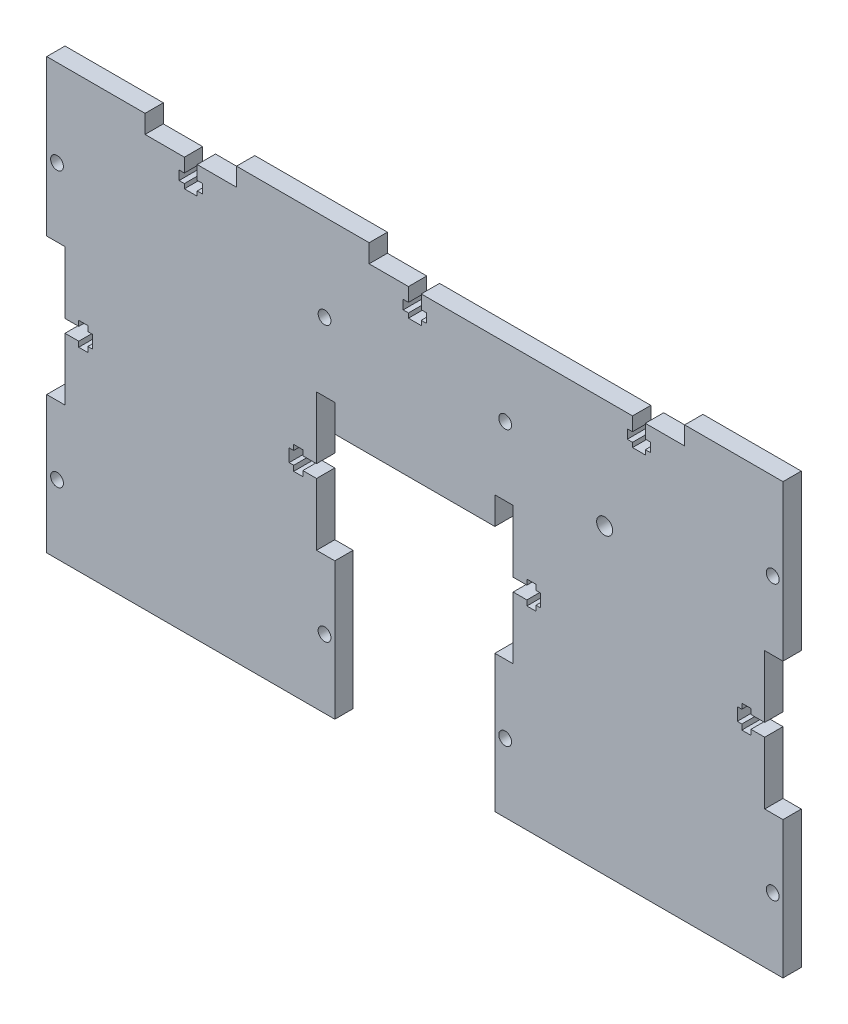
SolidWorks part; units mm, degrees
ref_plane "Спереди" through (0, 0, 0) normal (0, 0, 1) x (1, 0, 0)
ref_plane "Сверху" through (0, 0, 0) normal (0, 1, 0) x (1, 0, 0)
ref_plane "Справа" through (0, 0, 0) normal (1, 0, 0) x (0, 0, -1)
sketch "Эскиз1" plane through (0, 0, 0) normal (0, 0, 1) x (1, 0, 0)
  line L0 (-78.25, -14) -> (-78.25, 16) construction
  line L22 (78.25, -44) -> (78.25, -74) construction
  line L47 (-26.5, -26.45) -> (-24.5, -31.55) construction
  line L76 (-17.5, -20) -> (17.5, -20)
  line L93 (-17.5, -20) -> (-17.5, 20)
  line L126 (-17.5, 20) -> (17.5, 20)
  line L135 (17.5, -20) -> (17.5, 20)
  line L136 (-17.5, -20) -> (17.5, 20) construction
  line L141 (-17.5, 20) -> (17.5, -20) construction
  line L154 (-17.5, 20) -> (-80.5, 20)
  line L167 (-17.5, 20) -> (-17.5, -74)
  line L168 (-17.5, -74) -> (-80.5, -74)
  line L169 (-80.5, 20) -> (-80.5, -74)
  line L186 (-80.5, -14) -> (-76.5, -14)
  line L191 (-80.5, -14) -> (-80.5, -44)
  line L192 (-80.5, -44) -> (-76.5, -44)
  line L193 (-76.5, -14) -> (-76.5, -44)
  line L198 (-49, -74) -> (-49, 16) construction
  line L199 (-80.5, -29) -> (-17.5, -29) construction
  line L201 (-70.5, -30.4) -> (-76.5, -30.4)
  line L202 (-70.5, -30.4) -> (-70.5, -27.6)
  line L203 (-70.5, -27.6) -> (-76.5, -27.6)
  line L204 (-76.5, -30.4) -> (-76.5, -27.6)
  line L205 (-70.5, -30.4) -> (-76.5, -27.6) construction
  line L206 (-70.5, -27.6) -> (-76.5, -30.4) construction
  line L207 (-71.5, -31.55) -> (-73.5, -31.55)
  line L208 (-71.5, -31.55) -> (-71.5, -26.45)
  line L209 (-71.5, -26.45) -> (-73.5, -26.45)
  line L210 (-73.5, -31.55) -> (-73.5, -26.45)
  line L211 (-71.5, -31.55) -> (-73.5, -26.45) construction
  line L212 (-71.5, -26.45) -> (-73.5, -31.55) construction
  line L216 (-59, 16) -> (-39, 16)
  line L221 (-59, 16) -> (-59, 20)
  line L222 (-59, 20) -> (-39, 20)
  line L223 (-39, 16) -> (-39, 20)
  line L224 (-59, 16) -> (-39, 20) construction
  line L225 (-59, 20) -> (-39, 16) construction
  line L226 (-10, 16) -> (10, 16)
  line L227 (-10, 16) -> (-10, 20)
  line L228 (-10, 20) -> (10, 20)
  line L229 (10, 16) -> (10, 20)
  line L230 (-10, 16) -> (10, 20) construction
  line L231 (-10, 20) -> (10, 16) construction
  line L232 (-26.5, -31.55) -> (-24.5, -26.45) construction
  line L233 (-27.5, -27.6) -> (-21.5, -30.4) construction
  line L234 (-27.5, -30.4) -> (-21.5, -27.6) construction
  line L235 (19.75, -44) -> (19.75, -74) construction
  line L236 (-19.75, -14) -> (-19.75, 16) construction
  line L237 (-24.5, -31.55) -> (-24.5, -26.45)
  line L238 (-26.5, -26.45) -> (-24.5, -26.45)
  line L239 (-26.5, -31.55) -> (-26.5, -26.45)
  line L240 (-26.5, -31.55) -> (-24.5, -31.55)
  line L241 (-21.5, -30.4) -> (-21.5, -27.6)
  line L242 (-27.5, -27.6) -> (-21.5, -27.6)
  line L243 (-27.5, -30.4) -> (-27.5, -27.6)
  line L244 (-27.5, -30.4) -> (-21.5, -30.4)
  line L245 (-21.5, -14) -> (-21.5, -44)
  line L246 (-17.5, -44) -> (-21.5, -44)
  line L247 (-17.5, -14) -> (-17.5, -44)
  line L248 (-17.5, -14) -> (-21.5, -14)
  line L249 (-17.5, 20) -> (-17.5, -74)
  line L250 (0, -55) -> (0, 55) construction
  line L251 (19.75, -14) -> (19.75, 16) construction
  line L252 (-19.75, -44) -> (-19.75, -74) construction
  line L253 (27.5, -30.4) -> (21.5, -27.6) construction
  line L254 (27.5, -27.6) -> (21.5, -30.4) construction
  line L255 (26.5, -31.55) -> (24.5, -26.45) construction
  line L256 (59, 20) -> (39, 16) construction
  line L257 (59, 16) -> (39, 20) construction
  line L258 (71.5, -26.45) -> (73.5, -31.55) construction
  line L259 (71.5, -31.55) -> (73.5, -26.45) construction
  line L260 (70.5, -27.6) -> (76.5, -30.4) construction
  line L261 (70.5, -30.4) -> (76.5, -27.6) construction
  line L262 (80.5, -27) -> (17.5, -27) construction
  line L263 (49, -74) -> (49, 16) construction
  line L264 (26.5, -26.45) -> (24.5, -31.55) construction
  line L265 (-78.25, -44) -> (-78.25, -74) construction
  line L266 (78.25, -14) -> (78.25, 16) construction
  line L267 (17.5, 20) -> (17.5, -74)
  line L268 (17.5, -14) -> (21.5, -14)
  line L269 (17.5, -14) -> (17.5, -44)
  line L270 (17.5, -44) -> (21.5, -44)
  line L271 (21.5, -14) -> (21.5, -44)
  line L272 (27.5, -30.4) -> (21.5, -30.4)
  line L273 (27.5, -30.4) -> (27.5, -27.6)
  line L274 (27.5, -27.6) -> (21.5, -27.6)
  line L275 (21.5, -30.4) -> (21.5, -27.6)
  line L276 (26.5, -31.55) -> (24.5, -31.55)
  line L277 (26.5, -31.55) -> (26.5, -26.45)
  line L278 (26.5, -26.45) -> (24.5, -26.45)
  line L279 (24.5, -31.55) -> (24.5, -26.45)
  line L280 (39, 16) -> (39, 20)
  line L281 (59, 20) -> (39, 20)
  line L282 (59, 16) -> (59, 20)
  line L283 (59, 16) -> (39, 16)
  line L284 (73.5, -31.55) -> (73.5, -26.45)
  line L285 (71.5, -26.45) -> (73.5, -26.45)
  line L286 (71.5, -31.55) -> (71.5, -26.45)
  line L287 (71.5, -31.55) -> (73.5, -31.55)
  line L288 (76.5, -30.4) -> (76.5, -27.6)
  line L289 (70.5, -27.6) -> (76.5, -27.6)
  line L290 (70.5, -30.4) -> (70.5, -27.6)
  line L291 (70.5, -30.4) -> (76.5, -30.4)
  line L292 (76.5, -14) -> (76.5, -44)
  line L293 (80.5, -44) -> (76.5, -44)
  line L294 (80.5, -14) -> (80.5, -44)
  line L295 (80.5, -14) -> (76.5, -14)
  line L296 (80.5, 20) -> (80.5, -74)
  line L297 (17.5, -74) -> (80.5, -74)
  line L298 (17.5, 20) -> (17.5, -74)
  line L299 (17.5, 20) -> (80.5, 20)
  line L300 (51.55, 13) -> (46.45, 11) construction
  line L301 (-50.4, 10) -> (-47.6, 10)
  line L302 (-50.4, 10) -> (-50.4, 16)
  line L303 (-50.4, 16) -> (-47.6, 16)
  line L304 (-47.6, 10) -> (-47.6, 16)
  line L305 (-50.4, 10) -> (-47.6, 16) construction
  line L306 (-50.4, 16) -> (-47.6, 10) construction
  line L307 (-51.55, 11) -> (-46.45, 11)
  line L308 (-51.55, 11) -> (-51.55, 13)
  line L309 (-51.55, 13) -> (-46.45, 13)
  line L310 (-46.45, 11) -> (-46.45, 13)
  line L311 (-51.55, 11) -> (-46.45, 13) construction
  line L312 (-51.55, 13) -> (-46.45, 11) construction
  line L313 (51.55, 11) -> (46.45, 13) construction
  line L314 (50.4, 16) -> (47.6, 10) construction
  line L315 (50.4, 10) -> (47.6, 16) construction
  line L316 (46.45, 11) -> (46.45, 13)
  line L317 (51.55, 13) -> (46.45, 13)
  line L318 (51.55, 11) -> (51.55, 13)
  line L319 (51.55, 11) -> (46.45, 11)
  line L320 (47.6, 10) -> (47.6, 16)
  line L321 (50.4, 16) -> (47.6, 16)
  line L322 (50.4, 10) -> (50.4, 16)
  line L323 (50.4, 10) -> (47.6, 10)
  line L324 (10, 16) -> (39, 16)
  line L325 (-1.4, 10) -> (1.4, 10)
  line L326 (-1.4, 10) -> (-1.4, 16)
  line L327 (-1.4, 16) -> (1.4, 16)
  line L328 (1.4, 10) -> (1.4, 16)
  line L329 (-1.4, 10) -> (1.4, 16) construction
  line L330 (-1.4, 16) -> (1.4, 10) construction
  line L331 (-2.55, 11) -> (2.55, 11)
  line L332 (-2.55, 11) -> (-2.55, 13)
  line L333 (-2.55, 13) -> (2.55, 13)
  line L334 (2.55, 11) -> (2.55, 13)
  line L335 (-2.55, 11) -> (2.55, 13) construction
  line L336 (-2.55, 13) -> (2.55, 11) construction
  circle A13 centre (-78.25, 1) radius 1.4
  circle A18 centre (-19.75, 1) radius 1.4
  circle A19 centre (19.75, 1) radius 1.4
  circle A22 centre (78.25, 1) radius 1.4
  circle A23 centre (78.25, -59) radius 1.4
  circle A24 centre (19.75, -59) radius 1.4
  circle A25 centre (-19.75, -59) radius 1.4
  circle A26 centre (-78.25, -59) radius 1.4
  circle A27 centre (41.5, -7.9) radius 1.75
  point P0 (0, 0)
  point P19 (-49, -29)
  point P22 (-73.5, -29)
  point P27 (-72.5, -29)
  point P36 (-49, 18)
  point P41 (0, 18)
  point P46 (-49, 12)
  point P67 (-25.5, -29)
  point P68 (-24.5, -29)
  point P122 (24.5, -29)
  point P123 (25.5, -29)
  point P124 (49, 18)
  point P125 (72.5, -29)
  point P126 (73.5, -29)
  point P127 (-49, 13)
  point P144 (49, 13)
  point P145 (49, 12)
  point P146 (0, 13)
  point P152 (0, 12)
  point P157 (-76.5, -29)
  dimension "D2" = 40
  dimension "D1" = 35
  dimension "D7" = 2.8
  dimension "D16" = 3
  dimension "D20" = 3.5
  dimension "D3" = 63
  dimension "D4" = 94
  dimension "D5" = 30
  dimension "D6" = 4
  dimension "D8" = 2.25
  dimension "D9" = 2.8
  dimension "D10" = 6
  dimension "D11" = 2
  dimension "D12" = 3
  dimension "D13" = 5.1
  dimension "D14" = 4
  dimension "D15" = 20
  dimension "D17" = 3
  dimension "D18" = 23.9
  dimension "D19" = 20
extrude "Бобышка-Вытянуть1" add sketch "Эскиз1" along normal blind 4
